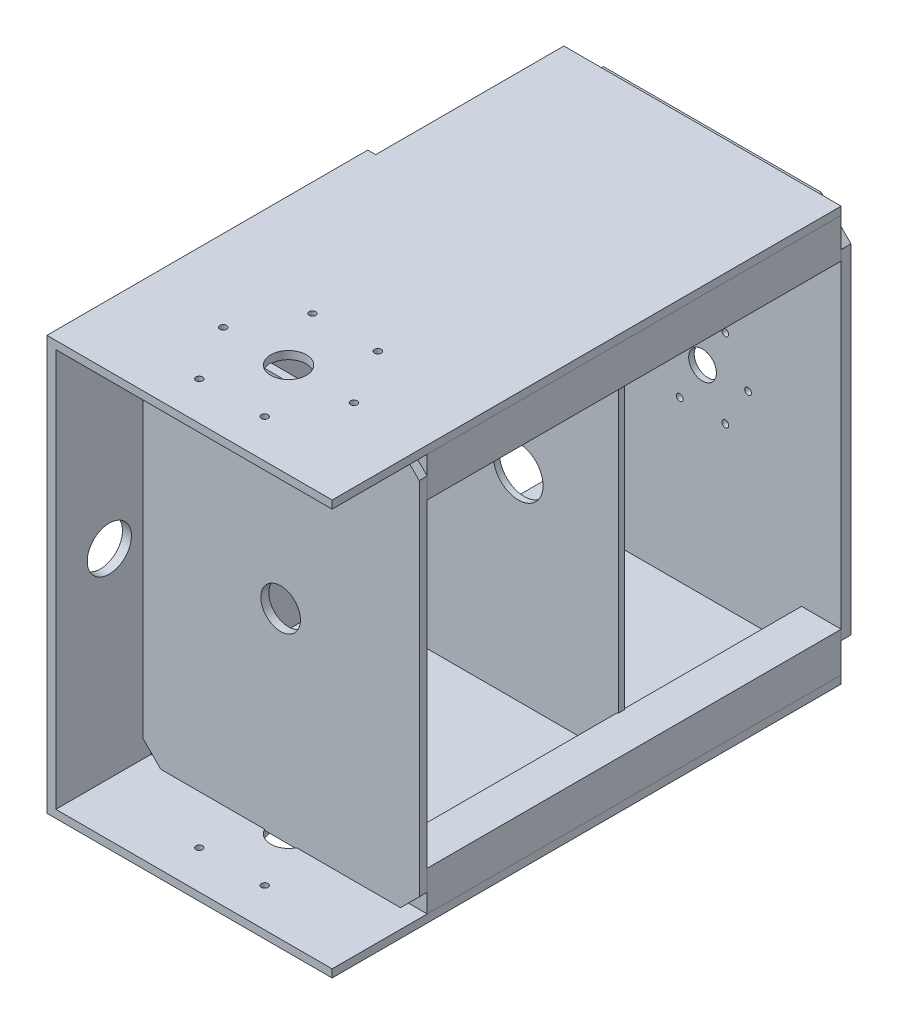
SolidWorks part; units mm, degrees
material "6061-T6 (SS)"
ref_plane "Front Plane" through (0, 0, 0) normal (0, 0, 1) x (1, 0, 0)
ref_plane "Top Plane" through (0, 0, 0) normal (0, 1, 0) x (1, 0, 0)
ref_plane "Right Plane" through (0, 0, 0) normal (1, 0, 0) x (0, 0, -1)
sketch "SK_Bottom_Plate" plane through (0, 0, 0) normal (0, 0, 1) x (1, 0, 0)
  line L0 (-55, -100.5) -> (55, -100.5)
  line L1 (55, -100.5) -> (70, -85.5)
  line L2 (70, -85.5) -> (70, 85.5)
  line L3 (70, 85.5) -> (55, 100.5)
  line L4 (55, 100.5) -> (-55, 100.5)
  line L5 (-55, 100.5) -> (-70, 85.5)
  line L6 (-70, 85.5) -> (-70, -85.5)
  line L7 (-70, -85.5) -> (-55, -100.5)
  circle A0 centre (23, 0) radius 1.7
  circle A1 centre (11.5, 19.9186) radius 1.7
  circle A2 centre (-11.5, 19.9186) radius 1.7
  circle A3 centre (-23, 0) radius 1.7
  circle A4 centre (-11.5, -19.9186) radius 1.7
  circle A5 centre (11.5, -19.9186) radius 1.7
  circle A6 centre (0, 0) radius 7
  circle A7 centre (60, 90.5) radius 2.75
  circle A8 centre (60, -90.5) radius 2.75
  circle A9 centre (-60, 90.5) radius 2.75
  circle A10 centre (-60, -90.5) radius 2.75
  dimension "D17_SK_Bottom_Plate" = 3.4
  dimension "D19_SK_Bottom_Plate" = 3.4
  dimension "D22_SK_Bottom_Plate" = 3.4
  dimension "D25_SK_Bottom_Plate" = 3.4
  dimension "D27_SK_Bottom_Plate" = 3.4
  dimension "D30_SK_Bottom_Plate" = 3.4
  dimension "D33_SK_Bottom_Plate" = 14
  dimension "D34_SK_Bottom_Plate" = 5.5
  dimension "D37_SK_Bottom_Plate" = 5.5
  dimension "D40_SK_Bottom_Plate" = 5.5
  dimension "D43_SK_Bottom_Plate" = 5.5
  dimension "P1" = 55
  dimension "P2" = 100.5
  dimension "P3" = 55
  dimension "P4" = 100.5
  dimension "P5" = 70
  dimension "P6" = 85.5
  dimension "P7" = 70
  dimension "P8" = 85.5
  dimension "P9" = 55
  dimension "P10" = 100.5
  dimension "P11" = 55
  dimension "P12" = 100.5
  dimension "P13" = 70
  dimension "P14" = 85.5
  dimension "P15" = 70
  dimension "P16" = 85.5
  dimension "P18" = 23
  dimension "P20" = 11.5
  dimension "P21" = 19.9186
  dimension "P23" = 11.5
  dimension "P24" = 19.9186
  dimension "P26" = 23
  dimension "P28" = 11.5
  dimension "P29" = 19.9186
  dimension "P31" = 11.5
  dimension "P32" = 19.9186
  dimension "P35" = 60
  dimension "P36" = 90.5
  dimension "P38" = 60
  dimension "P39" = 90.5
  dimension "P41" = 60
  dimension "P42" = 90.5
  dimension "P44" = 60
  dimension "P45" = 90.5
extrude "Bottom_Plate" add sketch "SK_Bottom_Plate" along normal blind 5
sketch "SK_Waist_Pilot_Recess" plane through (0, 0, 0) normal (0, 0, 1) x (1, 0, 0)
  circle A0 centre (0, 0) radius 17.15
  dimension "D1_SK_Waist_Pilot_Recess" = 34.3
extrude "Waist_Pilot_Recess" cut sketch "SK_Waist_Pilot_Recess" along normal blind 2.2
ref_plane "PL_Side_Left_base" through (0, 100.5, 0) normal (0, 1, 0) x (1, 0, 0)
sketch "SK_Side_Left" plane through (0, 100.5, 0) normal (0, 1, 0) x (1, 0, 0)
  line L0 (-70, -5) -> (70, -5)
  line L1 (70, -5) -> (70, -262)
  line L2 (70, -262) -> (-70, -262)
  line L3 (-70, -262) -> (-70, -5)
  circle A0 centre (33, -214) radius 1.7
  circle A1 centre (16.5, -185.4212) radius 1.7
  circle A2 centre (-16.5, -185.4212) radius 1.7
  circle A3 centre (-33, -214) radius 1.7
  circle A4 centre (-16.5, -242.5788) radius 1.7
  circle A5 centre (16.5, -242.5788) radius 1.7
  circle A6 centre (0, -214) radius 9
  dimension "D9_SK_Side_Left" = 3.4
  dimension "D12_SK_Side_Left" = 3.4
  dimension "D15_SK_Side_Left" = 3.4
  dimension "D18_SK_Side_Left" = 3.4
  dimension "D21_SK_Side_Left" = 3.4
  dimension "D24_SK_Side_Left" = 3.4
  dimension "D27_SK_Side_Left" = 18
  dimension "P1" = 70
  dimension "P2" = 5
  dimension "P3" = 70
  dimension "P4" = 5
  dimension "P5" = 70
  dimension "P6" = 262
  dimension "P7" = 70
  dimension "P8" = 262
  dimension "P10" = 33
  dimension "P11" = 214
  dimension "P13" = 16.5
  dimension "P14" = 185.4212
  dimension "P16" = 16.5
  dimension "P17" = 185.4212
  dimension "P19" = 33
  dimension "P20" = 214
  dimension "P22" = 16.5
  dimension "P23" = 242.5788
  dimension "P25" = 16.5
  dimension "P26" = 242.5788
  dimension "P28" = 214
extrude "Side_Left" add sketch "SK_Side_Left" along normal blind 4
ref_plane "PL_Side_Right_base" through (0, -104.5, 0) normal (0, 1, 0) x (1, 0, 0)
sketch "SK_Side_Right" plane through (0, -104.5, 0) normal (0, 1, 0) x (1, 0, 0)
  line L0 (-70, -5) -> (70, -5)
  line L1 (70, -5) -> (70, -262)
  line L2 (70, -262) -> (-70, -262)
  line L3 (-70, -262) -> (-70, -5)
  circle A0 centre (33, -214) radius 1.7
  circle A1 centre (16.5, -185.4212) radius 1.7
  circle A2 centre (-16.5, -185.4212) radius 1.7
  circle A3 centre (-33, -214) radius 1.7
  circle A4 centre (-16.5, -242.5788) radius 1.7
  circle A5 centre (16.5, -242.5788) radius 1.7
  circle A6 centre (0, -214) radius 9
  dimension "D9_SK_Side_Right" = 3.4
  dimension "D12_SK_Side_Right" = 3.4
  dimension "D15_SK_Side_Right" = 3.4
  dimension "D18_SK_Side_Right" = 3.4
  dimension "D21_SK_Side_Right" = 3.4
  dimension "D24_SK_Side_Right" = 3.4
  dimension "D27_SK_Side_Right" = 18
  dimension "P1" = 70
  dimension "P2" = 5
  dimension "P3" = 70
  dimension "P4" = 5
  dimension "P5" = 70
  dimension "P6" = 262
  dimension "P7" = 70
  dimension "P8" = 262
  dimension "P10" = 33
  dimension "P11" = 214
  dimension "P13" = 16.5
  dimension "P14" = 185.4212
  dimension "P16" = 16.5
  dimension "P17" = 185.4212
  dimension "P19" = 33
  dimension "P20" = 214
  dimension "P22" = 16.5
  dimension "P23" = 242.5788
  dimension "P25" = 16.5
  dimension "P26" = 242.5788
  dimension "P28" = 214
extrude "Side_Right" add sketch "SK_Side_Right" along normal blind 4
ref_plane "PL_Deck_base" through (0, 0, 214) normal (0, 0, 1) x (1, 0, 0)
sketch "SK_Deck" plane through (0, 0, 214) normal (0, 0, 1) x (1, 0, 0)
  line L0 (-60, -101) -> (60, -101)
  line L1 (60, -101) -> (70, -91)
  line L2 (70, -91) -> (70, 91)
  line L3 (70, 91) -> (60, 101)
  line L4 (60, 101) -> (-60, 101)
  line L5 (-60, 101) -> (-70, 91)
  line L6 (-70, 91) -> (-70, -91)
  line L7 (-70, -91) -> (-60, -101)
  circle A0 centre (0, 0) radius 10
  dimension "D17_SK_Deck" = 20
  dimension "P1" = 60
  dimension "P2" = 101
  dimension "P3" = 60
  dimension "P4" = 101
  dimension "P5" = 70
  dimension "P6" = 91
  dimension "P7" = 70
  dimension "P8" = 91
  dimension "P9" = 60
  dimension "P10" = 101
  dimension "P11" = 60
  dimension "P12" = 101
  dimension "P13" = 70
  dimension "P14" = 91
  dimension "P15" = 70
  dimension "P16" = 91
extrude "Deck" add sketch "SK_Deck" along normal blind 4
ref_plane "PL_Tray_base" through (0, 0, 95) normal (0, 0, 1) x (1, 0, 0)
sketch "SK_Tray" plane through (0, 0, 95) normal (0, 0, 1) x (1, 0, 0)
  line L0 (-50.5, -101) -> (50.5, -101)
  line L1 (50.5, -101) -> (50.5, 101)
  line L2 (50.5, 101) -> (-50.5, 101)
  line L3 (-50.5, 101) -> (-50.5, -101)
  circle A0 centre (0, 0) radius 12.5
  dimension "D9_SK_Tray" = 25
  dimension "P1" = 50.5
  dimension "P2" = 101
  dimension "P3" = 50.5
  dimension "P4" = 101
  dimension "P5" = 50.5
  dimension "P6" = 101
  dimension "P7" = 50.5
  dimension "P8" = 101
extrude "Tray" add sketch "SK_Tray" along normal blind 3
ref_plane "PL_Back_Plate_base" through (-74, 0, 0) normal (1, 0, 0) x (0, 0, -1)
sketch "SK_Back_Plate" plane through (-74, 0, 0) normal (1, 0, 0) x (0, 0, -1)
  line L0 (-100, -104.5) -> (-100, 104.5)
  line L1 (-100, 104.5) -> (-262, 104.5)
  line L2 (-262, 104.5) -> (-262, -104.5)
  line L3 (-262, -104.5) -> (-100, -104.5)
  circle A0 centre (-235, 0) radius 11.15
  dimension "D9_SK_Back_Plate" = 22.3
  dimension "P1" = 100
  dimension "P2" = 104.5
  dimension "P3" = 100
  dimension "P4" = 104.5
  dimension "P5" = 262
  dimension "P6" = 104.5
  dimension "P7" = 262
  dimension "P8" = 104.5
  dimension "P10" = 235
extrude "Back_Plate" add sketch "SK_Back_Plate" along normal blind 4.5
ref_plane "PL_Post_0_base" through (0, 0, 5) normal (0, 0, 1) x (1, 0, 0)
sketch "SK_Post_0" plane through (0, 0, 5) normal (0, 0, 1) x (1, 0, 0)
  line L0 (50, 80.5) -> (70, 80.5)
  line L1 (70, 80.5) -> (70, 100.5)
  line L2 (70, 100.5) -> (50, 100.5)
  line L3 (50, 100.5) -> (50, 80.5)
  dimension "P1" = 50
  dimension "P2" = 80.5
  dimension "P3" = 70
  dimension "P4" = 80.5
  dimension "P5" = 70
  dimension "P6" = 100.5
  dimension "P7" = 50
  dimension "P8" = 100.5
extrude "Post_0" add sketch "SK_Post_0" along normal blind 209 separate body
ref_plane "PL_Post_1_base" through (0, 0, 5) normal (0, 0, 1) x (1, 0, 0)
sketch "SK_Post_1" plane through (0, 0, 5) normal (0, 0, 1) x (1, 0, 0)
  line L0 (50, -100.5) -> (70, -100.5)
  line L1 (70, -100.5) -> (70, -80.5)
  line L2 (70, -80.5) -> (50, -80.5)
  line L3 (50, -80.5) -> (50, -100.5)
  dimension "P1" = 50
  dimension "P2" = 100.5
  dimension "P3" = 70
  dimension "P4" = 100.5
  dimension "P5" = 70
  dimension "P6" = 80.5
  dimension "P7" = 50
  dimension "P8" = 80.5
extrude "Post_1" add sketch "SK_Post_1" along normal blind 209 separate body
ref_plane "PL_Post_2_base" through (0, 0, 5) normal (0, 0, 1) x (1, 0, 0)
sketch "SK_Post_2" plane through (0, 0, 5) normal (0, 0, 1) x (1, 0, 0)
  line L0 (-70, 80.5) -> (-50, 80.5)
  line L1 (-50, 80.5) -> (-50, 100.5)
  line L2 (-50, 100.5) -> (-70, 100.5)
  line L3 (-70, 100.5) -> (-70, 80.5)
  dimension "P1" = 70
  dimension "P2" = 80.5
  dimension "P3" = 50
  dimension "P4" = 80.5
  dimension "P5" = 50
  dimension "P6" = 100.5
  dimension "P7" = 70
  dimension "P8" = 100.5
extrude "Post_2" add sketch "SK_Post_2" along normal blind 209 separate body
ref_plane "PL_Post_3_base" through (0, 0, 5) normal (0, 0, 1) x (1, 0, 0)
sketch "SK_Post_3" plane through (0, 0, 5) normal (0, 0, 1) x (1, 0, 0)
  line L0 (-70, -100.5) -> (-50, -100.5)
  line L1 (-50, -100.5) -> (-50, -80.5)
  line L2 (-50, -80.5) -> (-70, -80.5)
  line L3 (-70, -80.5) -> (-70, -100.5)
  dimension "P1" = 70
  dimension "P2" = 100.5
  dimension "P3" = 50
  dimension "P4" = 100.5
  dimension "P5" = 50
  dimension "P6" = 80.5
  dimension "P7" = 70
  dimension "P8" = 80.5
extrude "Post_3" add sketch "SK_Post_3" along normal blind 209 separate body
equation "\"Torso_half_depth\"= 70"
equation "\"Side_plate_y\"= 104.5"
equation "\"Shoulder_z\"= 214"
equation "\"Deck_z\"= 214"
